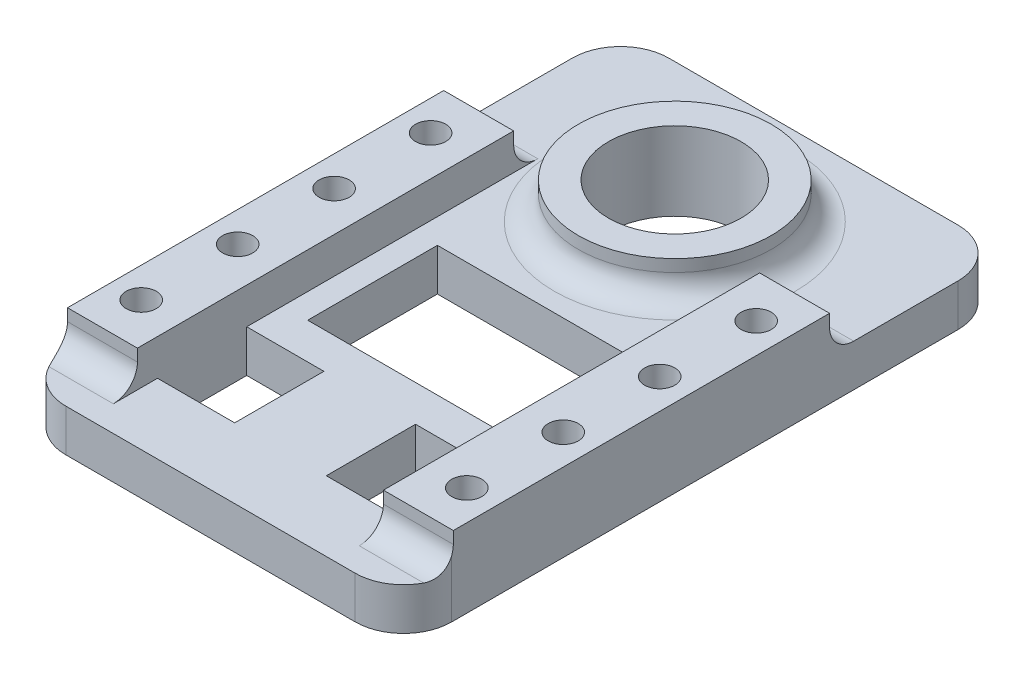
SolidWorks part; units mm, degrees
ref_plane "Plano frontal" through (0, 0, 0) normal (0, 0, 1) x (1, 0, 0)
ref_plane "Plano superior" through (0, 0, 0) normal (0, 1, 0) x (1, 0, 0)
ref_plane "Plano direito" through (0, 0, 0) normal (1, 0, 0) x (0, 0, -1)
sketch "Sketch1" plane through (0, 0, 0) normal (0, 1, 0) x (1, 0, 0)
  line L0 (-16, -25) -> (-16, -15.5) construction
  line L1 (-16, -25) -> (16, -25)
  line L2 (-16, -25) -> (-16, 25)
  line L3 (-16, 25) -> (16, 25)
  line L4 (16, -25) -> (16, 25)
  line L5 (-16, -25) -> (16, 25) construction
  line L6 (-16, 25) -> (16, -25) construction
  line L7 (-16, -15.5) -> (16, -15.5) construction
  line L8 (0, -15.5) -> (3.8, -15.5) construction
  line L9 (3.8, -15.5) -> (3.8, -11.8)
  line L10 (3.8, -11.8) -> (10.2, -11.8)
  line L11 (10.2, -11.8) -> (10.2, -19.2)
  line L12 (10.2, -19.2) -> (3.8, -19.2)
  line L13 (3.8, -19.2) -> (3.8, -15.5)
  line L15 (0, -55) -> (0, 55) construction
  line L16 (-10.2, -19.2) -> (-3.8, -19.2)
  line L17 (-10.2, -11.8) -> (-10.2, -19.2)
  line L18 (-3.8, -11.8) -> (-10.2, -11.8)
  line L19 (-3.8, -19.2) -> (-3.8, -15.5)
  line L20 (-3.8, -15.5) -> (-3.8, -11.8)
  line L21 (-16, 25) -> (-16, 13.5) construction
  line L22 (-16, 13.5) -> (16, 13.5) construction
  line L23 (0, 25) -> (0, 6.75) construction
  line L24 (0, 6.75) -> (13.5, 6.75) construction
  circle A0 centre (0, 13.5) radius 5.5
  circle A1 centre (13.5, 6.75) radius 1.25
  circle A2 centre (13.5, -1.25) radius 1.25
  circle A3 centre (13.5, -9.25) radius 1.25
  circle A4 centre (13.5, -17.25) radius 1.25
  circle A5 centre (-13.5, -17.25) radius 1.25
  circle A6 centre (-13.5, -9.25) radius 1.25
  circle A7 centre (-13.5, -1.25) radius 1.25
  circle A8 centre (-13.5, 6.75) radius 1.25
  point P0 (0, 0)
  dimension "D6" = 11
  dimension "D11" = 2.5
  dimension "D1" = 50
  dimension "D2" = 32
  dimension "D3" = 3.8
  dimension "D4" = 7.4
  dimension "D5" = 6.4
  dimension "D7" = 11.5
  dimension "D8" = 29
  dimension "D9" = 18.25
  dimension "D10" = 13.5
  dimension "D13" = 8
  dimension "D12" = 4
extrude "Boss-Extrude1" add sketch "Sketch1" along normal blind 3.5
fillet "Filete1" radius 4 4 edges at (16, 1.75, 25) (-16, 1.75, 25) (-16, 1.75, -25) (16, 1.75, -25)
sketch "Esboço1" plane through (0, 3.5, 0) normal (0, 1, 0) x (1, 0, 0)
  line L0 (0, 25) -> (0, -25) construction
  line L1 (12, 25) -> (-12, 25) construction
  line L2 (-12, -25) -> (12, -25) construction
  line L4 (-16, 10.3364) -> (-10.2, 10.3364)
  line L5 (-16, 10.3364) -> (-16, -20.8648)
  line L6 (-16, -20.8648) -> (-10.2, -20.8648)
  line L7 (-10.2, 10.3364) -> (-10.2, -20.8648)
  line L8 (-10.2, -11.8) -> (-10.2, -19.2) construction
  line L9 (16, -20.8648) -> (10.2, -20.8648)
  line L10 (10.2, 10.3364) -> (10.2, -20.8648)
  line L11 (16, 10.3364) -> (10.2, 10.3364)
  line L12 (16, 10.3364) -> (16, -20.8648)
  circle A0 centre (0, 13.5) radius 8
  circle A1 centre (0, 13.5) radius 5.5
extrude "Ressalto-extrusão1" add sketch "Esboço1" along normal blind 3
sketch "Esboço3" plane through (0, 3.5, 0) normal (0, 1, 0) x (1, 0, 0)
  line L0 (-10.2, 3.813) -> (10.2, 3.813) construction
  line L1 (-10.2, -20.8648) -> (-10.2, 10.3364) construction
  line L2 (10.2, 10.3364) -> (10.2, -20.8648) construction
  line L3 (0, 3.813) -> (0, 1.9576) construction
  line L4 (8.1445, 1.9576) -> (8.1445, -8.8)
  line L5 (-8.1445, 1.9576) -> (8.1445, 1.9576)
  line L6 (-8.1445, 1.9576) -> (-8.1445, -8.8)
  line L7 (-8.1445, -8.8) -> (8.1445, -8.8)
  line L9 (0, -8.8) -> (0, -12.5154) construction
  line L10 (10.2, -11.8) -> (3.8, -11.8) construction
  dimension "D1" = 3
extrude "Corte-extrusão1" cut sketch "Esboço3" against normal through all
sketch "Esboço4" plane through (0, 0, 0) normal (0, -1, 0) x (1, 0, 0)
  line L0 (0, 25) -> (0, 8.8) construction
  line L1 (-12, 25) -> (12, 25) construction
  line L2 (-8.1445, 8.8) -> (8.1445, 8.8) construction
  circle A0 centre (-13.5, 17.25) radius 1.25
  circle A1 centre (-13.5, 9.25) radius 1.25
  circle A2 centre (-13.5, 1.25) radius 1.25
  circle A3 centre (-13.5, -6.75) radius 1.25
  circle A4 centre (13.5, 1.25) radius 1.25
  circle A5 centre (13.5, 9.25) radius 1.25
  circle A6 centre (13.5, 17.25) radius 1.25
  circle A7 centre (13.5, -6.75) radius 1.25
extrude "Corte-extrusão2" cut sketch "Esboço4" against normal up to next
fillet "Filete2" radius 2 5 edges at (0, 3.5, -21.5) (13.1, 3.5, 20.8648) (-13.1, 3.5, 20.8648) (-13.1, 3.5, -10.3364) (13.1, 3.5, -10.3364)
